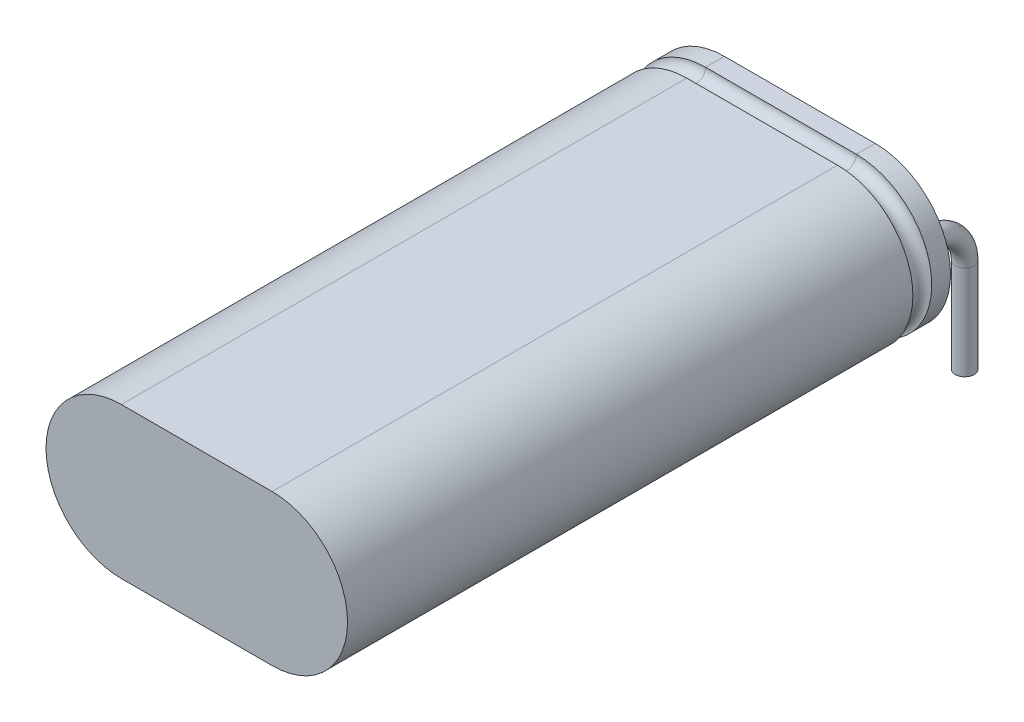
SolidWorks part; units mm, degrees
ref_plane "Front Plane" through (0, 0, 0) normal (0, 0, 1) x (1, 0, 0)
ref_plane "Top Plane" through (0, 0, 0) normal (0, 1, 0) x (1, 0, 0)
ref_plane "Right Plane" through (0, 0, 0) normal (1, 0, 0) x (0, 0, -1)
sketch "Sketch3" plane through (0, 0, 0) normal (1, 0, 0) x (0, 0, -1)
  line L0 (-32, 4) -> (-2, 4)
  line L1 (-1, 4) -> (0, 4)
  line L2 (0, 4) -> (0, 0)
  line L3 (-32, 4) -> (-32, 0)
  line L4 (-32, 0) -> (0, 0)
  line L5 (-32.6039, 0) -> (5.4215, 0) construction
  arc A0 (-2, 4) -> (-1, 4) centre (-1.5, 4) ccw
  dimension "D4" = 0.5
  dimension "D1" = 4
  dimension "D2" = 32
  dimension "D3" = 1
revolve "Revolve1" add sketch "Sketch3" angle 180 about L5
ref_plane "Plane1" through (1.75, 0, 0) normal (-1, 0, 0) x (0, 0, 1)
sketch "Sketch4" plane through (0, 0, 0) normal (-1, 0, 0) x (0, 0, 1)
  line L0 (0, 4) -> (0, -4)
  line L1 (0, -4) -> (1, -4)
  line L2 (2, -4) -> (32, -4)
  line L3 (32, -4) -> (32, 4)
  line L4 (32, 4) -> (2, 4)
  line L5 (1, 4) -> (0, 4)
  arc A0 (1, -4) -> (2, -4) centre (1.5, -4) cw
  arc A1 (2, 4) -> (1, 4) centre (1.5, 4) cw
extrude "Boss-Extrude2" add sketch "Sketch4" along normal blind 8
ref_plane "Plane2" through (-9.75, 0, 0) normal (-1, 0, 0) x (0, 0, 1)
sketch "Sketch14" plane through (-9.75, 0, 0) normal (-1, 0, 0) x (0, 0, 1)
  line L0 (0, 0) -> (-1, 0)
  line L1 (-3, -2) -> (-3, -7)
  arc A0 (-1, 0) -> (-3, -2) centre (-1, -2) ccw
  point P5 (-2.1556, -1.4925)
  dimension "D1" = 1
  dimension "D2" = 3
  dimension "D3" = 5
sketch "Sketch5" plane through (-8, 0, 0) normal (-1, 0, 0) x (0, 0, 1)
  line L0 (0, 0) -> (0, 4)
  line L1 (0, 4) -> (1, 4)
  line L2 (2, 4) -> (32, 4)
  line L3 (32, 4) -> (32, 0)
  line L4 (32, -4) -> (32, 4) construction
  line L5 (32, 0) -> (0, 0)
  line L6 (-3.0439, 0) -> (31.1948, 0) construction
  arc A0 (1, 4) -> (2, 4) centre (1.5, 4) ccw
revolve "Revolve2" add sketch "Sketch5" angle 180 about L6
sketch "Sketch7" plane through (1.75, 0, 0) normal (1, 0, 0) x (0, 0, -1)
  line L0 (0, 0) -> (1, 0)
  line L1 (3, -2) -> (3, -7)
  arc A0 (1, 0) -> (3, -2) centre (1, -2) cw
  point P5 (1.0499, -0.9501)
  dimension "D1" = 3
  dimension "D2" = 1
  dimension "D3" = 5
sweep "Sweep1" add path "Sketch7" circular profile diameter 1 parameters "D3"=1
sweep "Sweep2" add path "Sketch14" circular profile diameter 1 parameters "D3"=1
